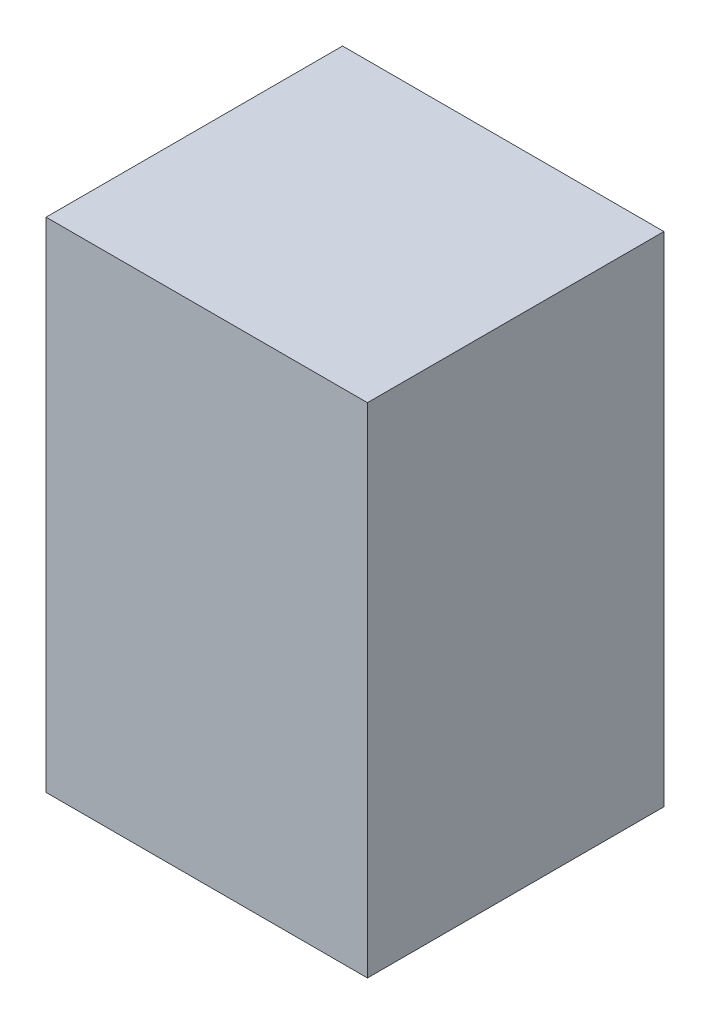
SolidWorks part; units mm, degrees
material "Perspex (TM) GS Acrylic Cast Sheet"
ref_plane "Front Plane" through (0, 0, 0) normal (0, 0, 1) x (1, 0, 0)
ref_plane "Top Plane" through (0, 0, 0) normal (0, 1, 0) x (1, 0, 0)
ref_plane "Right Plane" through (0, 0, 0) normal (1, 0, 0) x (0, 0, -1)
sketch "Sketch1" plane through (0, 0, 0) normal (0, 1, 0) x (1, 0, 0)
  line L1 (0, 0) -> (1638.3, 0)
  line L2 (0, 0) -> (0, 1511.3)
  line L3 (0, 1511.3) -> (1638.3, 1511.3)
  line L4 (1638.3, 0) -> (1638.3, 1511.3)
  dimension "D1" = 1511.3
  dimension "D2" = 1638.3
extrude "Boss-Extrude1" add sketch "Sketch1" along normal blind 2540
